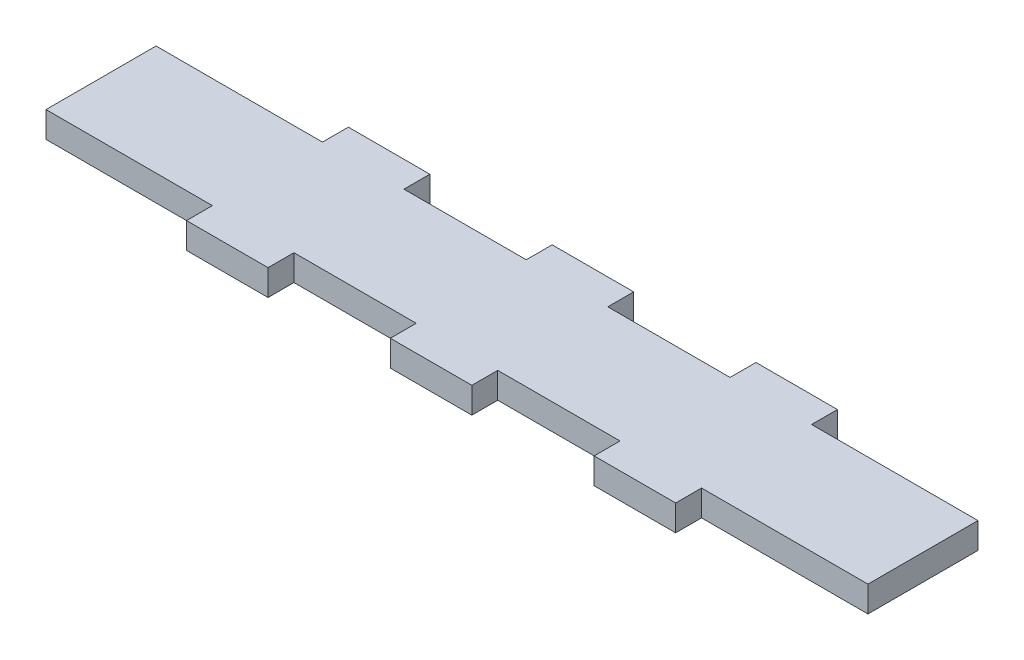
SolidWorks part; units mm, degrees
ref_plane "Front Plane" through (0, 0, 0) normal (0, 0, 1) x (1, 0, 0)
ref_plane "Top Plane" through (0, 0, 0) normal (0, 1, 0) x (1, 0, 0)
ref_plane "Right Plane" through (0, 0, 0) normal (1, 0, 0) x (0, 0, -1)
sketch "Sketch1" plane through (0, 0, 0) normal (0, 1, 0) x (1, 0, 0)
  line L0 (-100.825, 13.5) -> (-60, 13.5)
  line L1 (-100.825, 13.5) -> (100.825, 13.5) construction
  line L2 (-100.825, 13.5) -> (-100.825, -13.5)
  line L3 (-100.825, -13.5) -> (100.825, -13.5) construction
  line L4 (100.825, 13.5) -> (100.825, -13.5)
  line L5 (-100.825, 13.5) -> (100.825, -13.5) construction
  line L6 (-100.825, -13.5) -> (100.825, 13.5) construction
  line L7 (-60, 13.5) -> (-60, 19.85)
  line L8 (-60, 19.85) -> (-40, 19.85)
  line L9 (-40, 19.85) -> (-40, 13.5)
  line L10 (-40, 13.5) -> (-10, 13.5)
  line L11 (-10, 13.5) -> (-10, 19.85)
  line L12 (-10, 19.85) -> (10, 19.85)
  line L13 (10, 19.85) -> (10, 13.5)
  line L14 (10, 13.5) -> (40, 13.5)
  line L15 (40, 13.5) -> (40, 19.85)
  line L16 (40, 19.85) -> (60, 19.85)
  line L17 (60, 19.85) -> (60, 13.5)
  line L18 (60, 13.5) -> (100.825, 13.5)
  line L19 (-100.825, 0) -> (100.825, 0) construction
  line L20 (-100.825, -13.5) -> (-60, -13.5)
  line L21 (60, -13.5) -> (100.825, -13.5)
  line L22 (60, -19.85) -> (60, -13.5)
  line L23 (40, -19.85) -> (60, -19.85)
  line L24 (40, -13.5) -> (40, -19.85)
  line L25 (10, -13.5) -> (40, -13.5)
  line L26 (10, -19.85) -> (10, -13.5)
  line L27 (-10, -19.85) -> (10, -19.85)
  line L28 (-10, -13.5) -> (-10, -19.85)
  line L29 (-40, -13.5) -> (-10, -13.5)
  line L30 (-40, -19.85) -> (-40, -13.5)
  line L31 (-60, -19.85) -> (-40, -19.85)
  line L32 (-60, -13.5) -> (-60, -19.85)
  point P0 (0, 0)
  point P12 (0, 19.85)
  dimension "D1" = 201.65
  dimension "D2" = 20
  dimension "D3" = 30
  dimension "D4" = 6.35
  dimension "D5" = 27
extrude "Boss-Extrude1" add sketch "Sketch1" along normal blind 6.35
